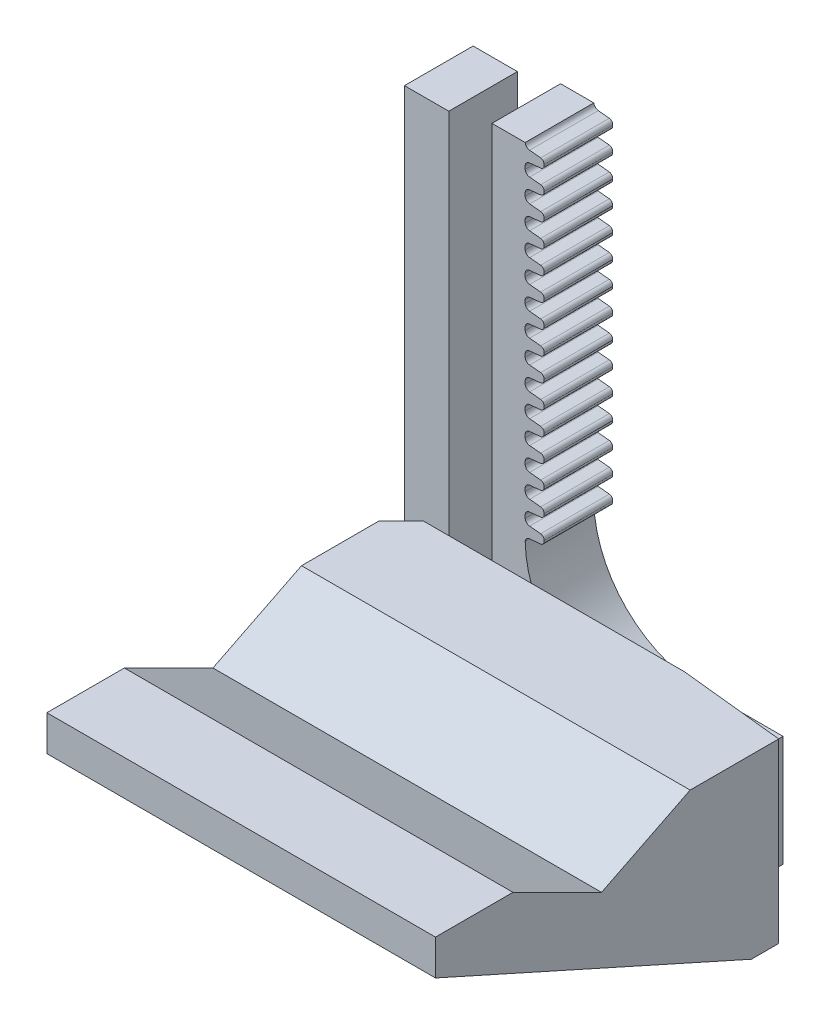
SolidWorks part; units mm, degrees
ref_plane "Front Plane" through (0, 0, 0) normal (0, 0, 1) x (1, 0, 0)
ref_plane "Top Plane" through (0, 0, 0) normal (0, 1, 0) x (1, 0, 0)
ref_plane "Right Plane" through (0, 0, 0) normal (1, 0, 0) x (0, 0, -1)
sketch "Sketch1" plane through (0, 0, 0) normal (0, 0, 1) x (1, 0, 0)
  line L1 (-28, 0) -> (0, 0)
  line L6 (-17.1, 20) -> (-17.1, 51)
  line L7 (-17.1, 51) -> (-20.1, 51)
  line L9 (0, 10) -> (-7.1, 10)
  line L11 (-20.1, 51) -> (-20.1, 6)
  line L12 (-28, 0) -> (-28, 50)
  line L13 (-28, 50) -> (-24, 50)
  line L14 (-24, 50) -> (-24, 6)
  line L15 (-24, 6) -> (-20.1, 6)
  line L16 (0, 10) -> (0, 0)
  arc A1 (-17.1, 20) -> (-7.1, 10) centre (-7.1, 20) ccw
  dimension "D8" = 10
  dimension "D1" = 45
  dimension "D2" = 3.9
  dimension "D3" = 3
  dimension "D4" = 4
  dimension "D5" = 50
  dimension "45" = 28
  dimension "D6" = 6
  dimension "D7" = 10
extrude "Boss-Extrude1" add sketch "Sketch1" along normal blind 6.2
sketch "Sketch2" plane through (0, 0, 0) normal (0, -1, 0) x (1, 0, 0)
  line L0 (0, 6.2) -> (0, 10.4)
  line L1 (0, 10.4) -> (11, 10.4)
  line L2 (11, 10.4) -> (11, 42.4)
  line L3 (11, 42.4) -> (-24.1, 42.4)
  line L4 (-24.1, 42.4) -> (-24.1, 10.4)
  line L5 (-24.1, 10.4) -> (-13.1, 10.4)
  line L6 (-13.1, 10.4) -> (-13.1, 6.2)
  line L7 (-28, 6.2) -> (0, 6.2) construction
  line L8 (-13.1, 6.2) -> (0, 6.2)
  dimension "D1" = 4.2
  dimension "D2" = 7
  dimension "D3" = 11
  dimension "D4" = 11
  dimension "D5" = 32
extrude "Boss-Extrude2" add sketch "Sketch2" against normal blind 21
chamfer "Chamfer1" distance 5 angle 80 1 edges at (-6.55, 0, 42.4)
sketch "Sketch3" plane through (0, 0, 0) normal (1, 0, 0) x (0, 0, -1)
  line L0 (-6.2, 10) -> (-7.6, 10)
  line L1 (-7.6, 10) -> (-10.4, 21)
  line L2 (-10.4, 21) -> (-6.2, 21)
  line L3 (-6.2, 21) -> (-6.2, 10)
  dimension "D1" = 1.4
extrude "Cut-Extrude1" cut sketch "Sketch3" against normal up to next
chamfer "Chamfer2" distance 1 angle 84 1 edges at (11, 10.5, 10.4)
chamfer "Chamfer3" distance 2 angle 45 1 edges at (-24.1, 10.5, 10.4)
sketch "Sketch5" plane through (11, 0, 0) normal (1, 0, 0) x (0, 0, -1)
  line L0 (-42.4, 17.8) -> (-13.8689, 5)
  line L1 (-42.4, 21) -> (-42.4, 5) construction
  line L3 (-13.8689, 5) -> (-10.9662, -4.1087)
  line L4 (-10.9662, -4.1087) -> (-44.0369, 0.9377)
  line L5 (-44.0369, 0.9377) -> (-42.4, 17.8)
  line L6 (-11.4, 21) -> (-10.4, 21) construction
  point P4 (-10.9662, -2.1087)
  point P12 (0, 0)
  point P13 (-11.4, -3.6703)
  point P14 (0, 0)
  dimension "D1" = 3.2
  dimension "D2" = 16
extrude "Cut-Extrude2" cut sketch "Sketch5" against normal up to next
sketch "Sketch6" plane through (0, 0, 10.4) normal (0, 0, -1) x (-1, 0, 0)
  line L0 (13.1, 0) -> (24.1, 5)
  line L1 (24.1, 5) -> (37.1983, 5)
  line L3 (-20.705, 5) -> (-11, 5)
  line L4 (-11, 5) -> (0, 0)
  line L5 (0, 0) -> (13.1, 0)
  line L6 (37.1983, 5) -> (28.626, -4.5222)
  line L7 (28.626, -4.5222) -> (-13.826, -5.6293)
  line L8 (-13.826, -5.6293) -> (-20.705, 5)
extrude "Cut-Extrude3" cut sketch "Sketch6" against normal up to next
sketch "Sketch7" plane through (0, 0, 6.2) normal (0, 0, 1) x (1, 0, 0)
  line L0 (-17.1, 20) -> (-17.1, 51) construction
  line L1 (-15.4, 50.1) -> (-17.4129, 50.1) construction
  line L2 (-16.7, 50.6) -> (-15.7, 50.5)
  line L3 (-16.7, 49.6) -> (-15.7, 49.7)
  line L4 (-17.1, 49.2) -> (-17.1, 48.9)
  line L5 (-17.1, 47.1) -> (-17.1, 46.8)
  line L6 (-16.7, 47.5) -> (-15.7, 47.6)
  line L7 (-16.7, 48.5) -> (-15.7, 48.4)
  line L8 (-17.1, 45) -> (-17.1, 44.7)
  line L9 (-16.7, 45.4) -> (-15.7, 45.5)
  line L10 (-16.7, 46.4) -> (-15.7, 46.3)
  line L11 (-17.1, 42.9) -> (-17.1, 42.6)
  line L12 (-16.7, 43.3) -> (-15.7, 43.4)
  line L13 (-16.7, 44.3) -> (-15.7, 44.2)
  line L14 (-17.1, 40.8) -> (-17.1, 40.5)
  line L15 (-16.7, 41.2) -> (-15.7, 41.3)
  line L16 (-16.7, 42.2) -> (-15.7, 42.1)
  line L17 (-17.1, 38.7) -> (-17.1, 38.4)
  line L18 (-16.7, 39.1) -> (-15.7, 39.2)
  line L19 (-16.7, 40.1) -> (-15.7, 40)
  line L20 (-17.1, 36.6) -> (-17.1, 36.3)
  line L21 (-16.7, 37) -> (-15.7, 37.1)
  line L22 (-16.7, 38) -> (-15.7, 37.9)
  line L23 (-17.1, 34.5) -> (-17.1, 34.2)
  line L24 (-16.7, 34.9) -> (-15.7, 35)
  line L25 (-16.7, 35.9) -> (-15.7, 35.8)
  line L26 (-17.1, 32.4) -> (-17.1, 32.1)
  line L27 (-16.7, 32.8) -> (-15.7, 32.9)
  line L28 (-16.7, 33.8) -> (-15.7, 33.7)
  line L29 (-17.1, 30.3) -> (-17.1, 30)
  line L30 (-16.7, 30.7) -> (-15.7, 30.8)
  line L31 (-16.7, 31.7) -> (-15.7, 31.6)
  line L32 (-17.1, 28.2) -> (-17.1, 27.9)
  line L33 (-16.7, 28.6) -> (-15.7, 28.7)
  line L34 (-16.7, 29.6) -> (-15.7, 29.5)
  line L35 (-17.1, 26.1) -> (-17.1, 25.8)
  line L36 (-16.7, 26.5) -> (-15.7, 26.6)
  line L37 (-16.7, 27.5) -> (-15.7, 27.4)
  line L38 (-17.1, 24) -> (-17.1, 23.7)
  line L39 (-16.7, 24.4) -> (-15.7, 24.5)
  line L40 (-16.7, 25.4) -> (-15.7, 25.3)
  line L41 (-17.1, 21.9) -> (-17.1, 21.6)
  line L42 (-16.7, 22.3) -> (-15.7, 22.4)
  line L43 (-16.7, 23.3) -> (-15.7, 23.2)
  line L44 (-17.1, 19.8) -> (-17.1, 19.5)
  line L45 (-16.7, 20.2) -> (-15.7, 20.3)
  line L46 (-16.7, 21.2) -> (-15.7, 21.1)
  line L47 (-17.1, 19.5) -> (-18.6374, 21.1263)
  line L48 (-18.6374, 21.1263) -> (-18.815, 46.4)
  line L49 (-18.815, 46.4) -> (-17.1, 51)
  arc A0 (-17.1, 51) -> (-16.7, 50.6) centre (-16.6556, 51.0444) ccw
  arc A1 (-15.7, 50.5) -> (-15.4, 50.1) centre (-15.7338, 50.1622) cw
  arc A2 (-17.1, 49.2) -> (-16.7, 49.6) centre (-16.6556, 49.1556) cw
  arc A3 (-15.7, 49.7) -> (-15.4, 50.1) centre (-15.7338, 50.0378) ccw
  arc A4 (-17.1, 47.1) -> (-16.7, 47.5) centre (-16.6556, 47.0556) cw
  arc A5 (-15.7, 47.6) -> (-15.4, 48) centre (-15.7338, 47.9378) ccw
  arc A6 (-15.7, 48.4) -> (-15.4, 48) centre (-15.7338, 48.0622) cw
  arc A7 (-17.1, 48.9) -> (-16.7, 48.5) centre (-16.6556, 48.9444) ccw
  arc A8 (-17.1, 45) -> (-16.7, 45.4) centre (-16.6556, 44.9556) cw
  arc A9 (-15.7, 45.5) -> (-15.4, 45.9) centre (-15.7338, 45.8378) ccw
  arc A10 (-15.7, 46.3) -> (-15.4, 45.9) centre (-15.7338, 45.9622) cw
  arc A11 (-17.1, 46.8) -> (-16.7, 46.4) centre (-16.6556, 46.8444) ccw
  arc A12 (-17.1, 42.9) -> (-16.7, 43.3) centre (-16.6556, 42.8556) cw
  arc A13 (-15.7, 43.4) -> (-15.4, 43.8) centre (-15.7338, 43.7378) ccw
  arc A14 (-15.7, 44.2) -> (-15.4, 43.8) centre (-15.7338, 43.8622) cw
  arc A15 (-17.1, 44.7) -> (-16.7, 44.3) centre (-16.6556, 44.7444) ccw
  arc A16 (-17.1, 40.8) -> (-16.7, 41.2) centre (-16.6556, 40.7556) cw
  arc A17 (-15.7, 41.3) -> (-15.4, 41.7) centre (-15.7338, 41.6378) ccw
  arc A18 (-15.7, 42.1) -> (-15.4, 41.7) centre (-15.7338, 41.7622) cw
  arc A19 (-17.1, 42.6) -> (-16.7, 42.2) centre (-16.6556, 42.6444) ccw
  arc A20 (-17.1, 38.7) -> (-16.7, 39.1) centre (-16.6556, 38.6556) cw
  arc A21 (-15.7, 39.2) -> (-15.4, 39.6) centre (-15.7338, 39.5378) ccw
  arc A22 (-15.7, 40) -> (-15.4, 39.6) centre (-15.7338, 39.6622) cw
  arc A23 (-17.1, 40.5) -> (-16.7, 40.1) centre (-16.6556, 40.5444) ccw
  arc A24 (-17.1, 36.6) -> (-16.7, 37) centre (-16.6556, 36.5556) cw
  arc A25 (-15.7, 37.1) -> (-15.4, 37.5) centre (-15.7338, 37.4378) ccw
  arc A26 (-15.7, 37.9) -> (-15.4, 37.5) centre (-15.7338, 37.5622) cw
  arc A27 (-17.1, 38.4) -> (-16.7, 38) centre (-16.6556, 38.4444) ccw
  arc A28 (-17.1, 34.5) -> (-16.7, 34.9) centre (-16.6556, 34.4556) cw
  arc A29 (-15.7, 35) -> (-15.4, 35.4) centre (-15.7338, 35.3378) ccw
  arc A30 (-15.7, 35.8) -> (-15.4, 35.4) centre (-15.7338, 35.4622) cw
  arc A31 (-17.1, 36.3) -> (-16.7, 35.9) centre (-16.6556, 36.3444) ccw
  arc A32 (-17.1, 32.4) -> (-16.7, 32.8) centre (-16.6556, 32.3556) cw
  arc A33 (-15.7, 32.9) -> (-15.4, 33.3) centre (-15.7338, 33.2378) ccw
  arc A34 (-15.7, 33.7) -> (-15.4, 33.3) centre (-15.7338, 33.3622) cw
  arc A35 (-17.1, 34.2) -> (-16.7, 33.8) centre (-16.6556, 34.2444) ccw
  arc A36 (-17.1, 30.3) -> (-16.7, 30.7) centre (-16.6556, 30.2556) cw
  arc A37 (-15.7, 30.8) -> (-15.4, 31.2) centre (-15.7338, 31.1378) ccw
  arc A38 (-15.7, 31.6) -> (-15.4, 31.2) centre (-15.7338, 31.2622) cw
  arc A39 (-17.1, 32.1) -> (-16.7, 31.7) centre (-16.6556, 32.1444) ccw
  arc A40 (-17.1, 28.2) -> (-16.7, 28.6) centre (-16.6556, 28.1556) cw
  arc A41 (-15.7, 28.7) -> (-15.4, 29.1) centre (-15.7338, 29.0378) ccw
  arc A42 (-15.7, 29.5) -> (-15.4, 29.1) centre (-15.7338, 29.1622) cw
  arc A43 (-17.1, 30) -> (-16.7, 29.6) centre (-16.6556, 30.0444) ccw
  arc A44 (-17.1, 26.1) -> (-16.7, 26.5) centre (-16.6556, 26.0556) cw
  arc A45 (-15.7, 26.6) -> (-15.4, 27) centre (-15.7338, 26.9378) ccw
  arc A46 (-15.7, 27.4) -> (-15.4, 27) centre (-15.7338, 27.0622) cw
  arc A47 (-17.1, 27.9) -> (-16.7, 27.5) centre (-16.6556, 27.9444) ccw
  arc A48 (-17.1, 24) -> (-16.7, 24.4) centre (-16.6556, 23.9556) cw
  arc A49 (-15.7, 24.5) -> (-15.4, 24.9) centre (-15.7338, 24.8378) ccw
  arc A50 (-15.7, 25.3) -> (-15.4, 24.9) centre (-15.7338, 24.9622) cw
  arc A51 (-17.1, 25.8) -> (-16.7, 25.4) centre (-16.6556, 25.8444) ccw
  arc A52 (-17.1, 21.9) -> (-16.7, 22.3) centre (-16.6556, 21.8556) cw
  arc A53 (-15.7, 22.4) -> (-15.4, 22.8) centre (-15.7338, 22.7378) ccw
  arc A54 (-15.7, 23.2) -> (-15.4, 22.8) centre (-15.7338, 22.8622) cw
  arc A55 (-17.1, 23.7) -> (-16.7, 23.3) centre (-16.6556, 23.7444) ccw
  arc A56 (-17.1, 19.8) -> (-16.7, 20.2) centre (-16.6556, 19.7556) cw
  arc A57 (-15.7, 20.3) -> (-15.4, 20.7) centre (-15.7338, 20.6378) ccw
  arc A58 (-15.7, 21.1) -> (-15.4, 20.7) centre (-15.7338, 20.7622) cw
  arc A59 (-17.1, 21.6) -> (-16.7, 21.2) centre (-16.6556, 21.6444) ccw
  point P186 (-17.1, 48.8834)
  dimension "D1" = 0.4
  dimension "D6" = 0.4
  dimension "D2" = 0.3
  dimension "D3" = 0.4
  dimension "D4" = 0.1
  dimension "D5" = 1
  dimension "D7" = 15
extrude "Boss-Extrude3" add sketch "Sketch7" against normal up to surface (6.2 mm away) up to face at (-17.0519, 22.9026, 0)
sketch "Sketch8" plane through (11, 0, 0) normal (1, 0, 0) x (0, 0, -1)
  line L0 (-35.4, 21) -> (-27.4, 17)
  line L1 (-11.4, 21) -> (-42.4, 21) construction
  line L2 (-27.4, 17) -> (-19.4, 21)
  line L3 (-19.4, 21) -> (-35.4, 21)
  dimension "D1" = 4
  dimension "D2" = 16
  dimension "D3" = 7
  dimension "D4" = 8
extrude "Cut-Extrude4" cut sketch "Sketch8" against normal up to next
equation "\"D4@Sketch8\"=\"D2@Sketch8\"/2"
